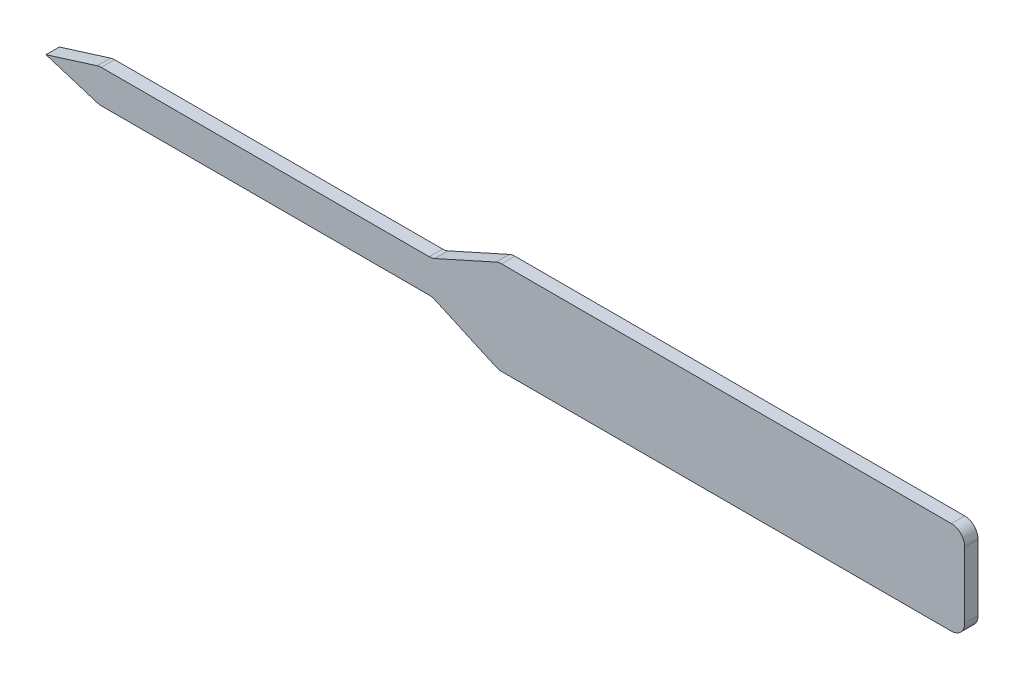
SolidWorks part; units mm, degrees
ref_plane "Front Plane" through (0, 0, 0) normal (0, 0, 1) x (1, 0, 0)
ref_plane "Top Plane" through (0, 0, 0) normal (0, 1, 0) x (1, 0, 0)
ref_plane "Right Plane" through (0, 0, 0) normal (1, 0, 0) x (0, 0, -1)
sketch "Sketch1" plane through (0, 0, 0) normal (0, 0, 1) x (1, 0, 0)
  line L0 (-35, 7) -> (-45, 2.5)
  line L1 (-35, 7) -> (35, 7)
  line L3 (-35, -7) -> (35, -7)
  line L4 (35, 7) -> (35, -7)
  line L5 (-35, 7) -> (35, -7) construction
  line L6 (-35, -7) -> (35, 7) construction
  line L7 (-45, -2.5) -> (-35, -7)
  line L8 (-95, 2.5) -> (-103, 0)
  line L9 (-95, 2.5) -> (-45, 2.5)
  line L11 (-95, -2.5) -> (-45, -2.5)
  line L13 (-95, 2.5) -> (-45, -2.5) construction
  line L14 (-95, -2.5) -> (-45, 2.5) construction
  line L15 (-103, 0) -> (-95, -2.5)
  point P0 (0, 0)
  point P6 (-70, 0)
  point P7 (0, 0)
  point P12 (0, 0)
  point P13 (0, 0)
  dimension "D1" = 14
  dimension "D2" = 70
  dimension "D3" = 5
  dimension "D4" = 8
  dimension "D5" = 10
  dimension "D6" = 50
extrude "Boss-Extrude1" add sketch "Sketch1" along normal blind 2
fillet "Fillet1" radius 2 8 edges at (35, -7, 1) (35, 7, 1) (-95, -2.5, 1) (-95, 2.5, 1) (-35, 7, 1) (-35, -7, 1) (-45, -2.5, 1) (-45, 2.5, 1)
